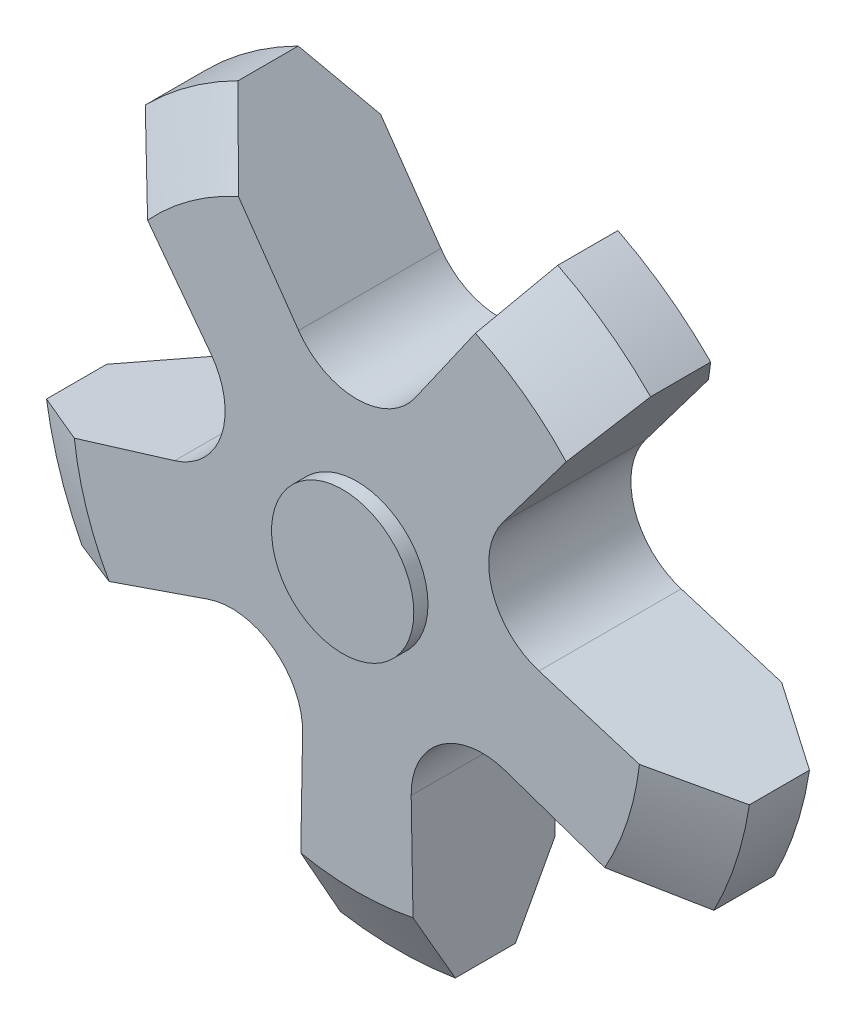
SolidWorks part; units mm, degrees
ref_plane "Front Plane" through (0, 0, 0) normal (0, 0, 1) x (1, 0, 0)
ref_plane "Top Plane" through (0, 0, 0) normal (0, 1, 0) x (1, 0, 0)
ref_plane "Right Plane" through (0, 0, 0) normal (1, 0, 0) x (0, 0, -1)
sketch "Sketch1" plane through (0, 0, 0) normal (0, 0, 1) x (1, 0, 0)
  circle A0 centre (0, 0) radius 25
  dimension "D1" = 50
extrude "Boss-Extrude1" add sketch "Sketch1" along normal blind 10
chamfer "Chamfer1" distance 5 angle 30 1 edges at (25, 0, 10)
chamfer "Chamfer2" distance 5 angle 30 1 edges at (25, 0, 0)
sketch "Sketch2" plane through (0, 0, 10) normal (0, 0, 1) x (1, 0, 0)
  line L0 (0, 0) -> (0, 15) construction
  line L1 (11.2377, 22.3319) -> (4.0958, 12.1321)
  line L2 (-11.2377, 22.3319) -> (-4.0958, 12.1321)
  arc A0 (-4.0958, 12.1321) -> (4.0958, 12.1321) centre (0, 15) ccw
  circle A1 centre (0, 0) radius 25 construction
  arc A2 (11.2377, 22.3319) -> (-11.2377, 22.3319) centre (0, 0) ccw
  dimension "D2" = 10
  dimension "D1" = 15
  dimension "D3" = 35
extrude "Cut-Extrude1" cut sketch "Sketch2" against normal through all
pattern_circular "CirPattern1" count 5 over 360 about axis through (0, 0, 0) along (0, 0, 1) of "Cut-Extrude1"
sketch "Sketch3" plane through (0, 0, 10) normal (0, 0, 1) x (1, 0, 0)
  circle A0 centre (0, 0) radius 5
  dimension "D1" = 10
extrude "Boss-Extrude2" add sketch "Sketch3" along normal blind 1 and the other way blind 12
